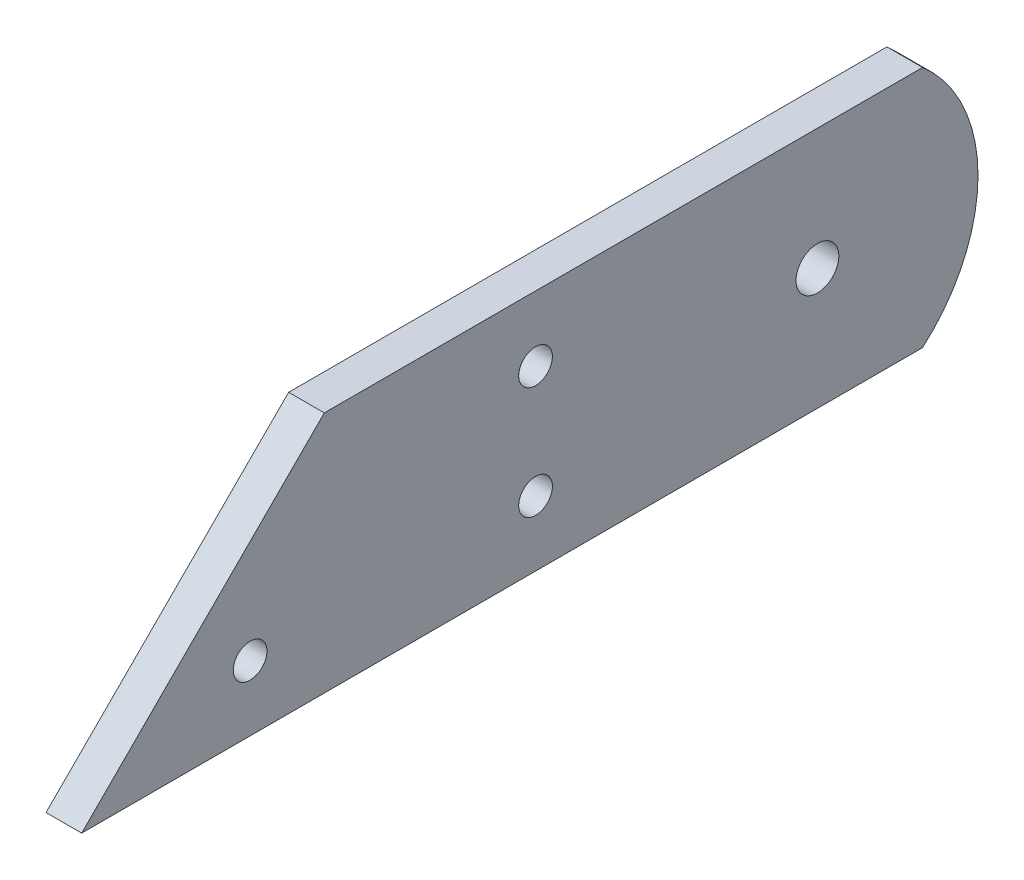
SolidWorks part; units mm, degrees
material "PE High Density"
ref_plane "Front Plane" through (0, 0, 0) normal (0, 0, 1) x (1, 0, 0)
ref_plane "Top Plane" through (0, 0, 0) normal (0, 1, 0) x (1, 0, 0)
ref_plane "Right Plane" through (0, 0, 0) normal (1, 0, 0) x (0, 0, -1)
sketch "Sketch1" plane through (0, 0, 0) normal (1, 0, 0) x (0, 0, -1)
  line L0 (-106.172, 0) -> (-62.992, 43.18)
  line L1 (0, 0) -> (-106.172, 0)
  line L2 (0, 0) -> (0, 2.54)
  line L3 (0, 43.18) -> (-62.992, 43.18)
  line L5 (0, 40.64) -> (-65.532, 40.64) construction
  line L6 (0, 2.54) -> (-103.632, 2.54) construction
  line L7 (0, 40.64) -> (0, 43.18)
  arc A0 (0, 40.64) -> (0, 2.54) centre (24.7621, 21.59) ccw
  dimension "D4" = 62.484
  dimension "D1" = 43.18
  dimension "D2" = 106.172
  dimension "D3" = 45
  dimension "D5" = 2.54
  dimension "D6" = 2.54
extrude "Boss-Extrude1" add sketch "Sketch1" along normal blind 6.35
sketch "Sketch2" plane through (6.35, 0, 0) normal (1, 0, 0) x (0, 0, -1)
  line L0 (-106.172, 0) -> (0, 0) construction
  line L1 (-68.072, 0) -> (-169.672, 0)
  line L2 (-169.672, 0) -> (-144.272, 10.16)
  line L3 (-144.272, 10.16) -> (-68.072, 17.78)
  line L4 (-68.072, 17.78) -> (-68.072, 0)
  dimension "D1" = 17.78
  dimension "D2" = 25.4
  dimension "D3" = 10.16
  dimension "D4" = 38.1
  dimension "D5" = 76.2
extrude "Boss-Extrude2" add sketch "Sketch2" against normal up to surface (6.35 mm away) up to face at (0, 21.59, 29.274)
sketch "Sketch3" plane through (6.35, 0, 0) normal (1, 0, 0) x (0, 0, -1)
  line L0 (-90.6498, 15.5222) -> (-106.172, 0) construction
  line L1 (-62.992, 43.18) -> (-90.6498, 15.5222) construction
  line L2 (-169.672, 0) -> (0, 0) construction
  line L3 (-106.172, 0) -> (-162.687, 2.794)
  line L4 (-144.272, 10.16) -> (-169.672, 0) construction
  line L5 (-162.687, 2.794) -> (-169.672, 0)
  line L6 (-169.672, 0) -> (-106.172, 0)
  dimension "D1" = 2.794
extrude "Cut-Extrude1" cut sketch "Sketch3" against normal through all
sketch "Sketch4" plane through (6.35, 0, 0) normal (1, 0, 0) x (0, 0, -1)
  line L1 (0, 0) -> (0, 2.54) construction
  line L2 (-25.4, 31.59) -> (-25.4, 11.59) construction
  circle A0 centre (-25.4, 31.59) radius 3
  circle A1 centre (-25.4, 11.59) radius 3
  arc A3 (0, 40.64) -> (0, 2.54) centre (24.7621, 21.59) ccw construction
  circle A4 centre (-76.2, 11.59) radius 3
  point P11 (-6.4799, 21.59)
  point P12 (-25.4, 21.59)
  dimension "D1" = 6
  dimension "D2" = 20
  dimension "D3" = 50.8
  dimension "D4" = 25.4
extrude "Cut-Extrude2" cut sketch "Sketch4" against normal through all
sketch "Sketch6" plane through (0, 0, 0) normal (-1, 0, 0) x (0, 0, 1)
  line L0 (62.992, 43.18) -> (90.6498, 15.5222)
  line L1 (90.6498, 15.5222) -> (108.3099, -2.1379)
  line L2 (108.3099, -2.1379) -> (165.3189, -0.9138)
  line L3 (165.3189, -0.9138) -> (157.2336, 13.29)
  line L4 (157.2336, 13.29) -> (95.2374, 20.1098)
  line L5 (95.2374, 20.1098) -> (62.992, 43.18)
extrude "Cut-Extrude3" cut sketch "Sketch6" against normal up to surface (6.35 mm away) up to face at (6.35, 31.59, 22.4)
sketch "Sketch7" plane through (0, 0, 0) normal (-1, 0, 0) x (0, 0, 1)
  line L0 (0, 43.18) -> (-43.4811, 43.18)
  line L1 (0, 0) -> (-43.4811, 0)
  line L2 (0, 0) -> (0, 2.54) construction
  line L3 (0, 40.64) -> (0, 43.18) construction
  line L4 (0, 0) -> (0, 2.54)
  line L5 (0, 40.64) -> (0, 43.18)
  arc A0 (-43.4811, 43.18) -> (-43.4811, 0) centre (-24.7621, 21.59) ccw
  arc A1 (0, 2.54) -> (0, 40.64) centre (-24.7621, 21.59) ccw construction
  circle A2 centre (-24.7621, 21.59) radius 3.81
  arc A3 (0, 2.54) -> (0, 40.64) centre (-24.7621, 21.59) ccw
  dimension "D1" = 57.15
  dimension "D2" = 7.62
extrude "Boss-Extrude3" add sketch "Sketch7" against normal up to surface (6.35 mm away) up to face at (6.35, 21.59, 29.274)
